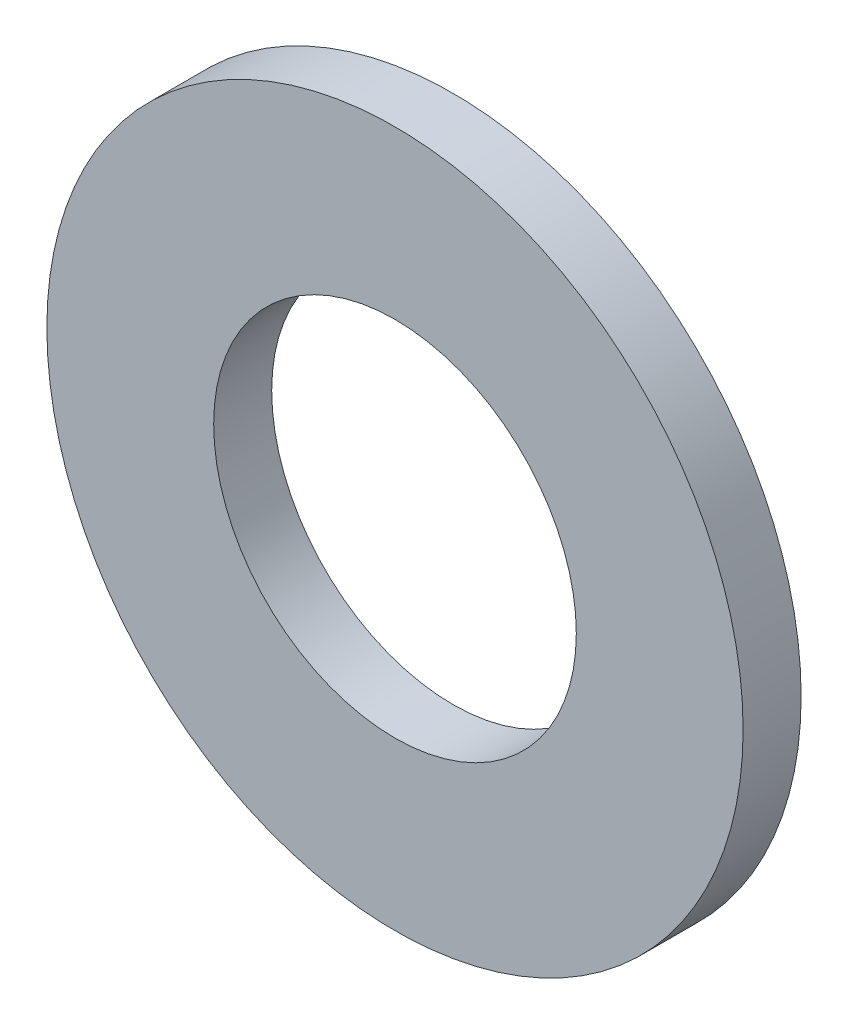
SolidWorks part; units mm, degrees
ref_plane "Ön Düzlem" through (0, 0, 0) normal (0, 0, 1) x (1, 0, 0)
ref_plane "Üst Düzlem" through (0, 0, 0) normal (0, 1, 0) x (1, 0, 0)
ref_plane "Sağ Düzlem" through (0, 0, 0) normal (1, 0, 0) x (0, 0, -1)
sketch "Çizim1" plane through (0, 0, 0) normal (0, 0, 1) x (1, 0, 0)
  circle A0 centre (0, 0) radius 6
  circle A1 centre (0, 0) radius 3.125
  dimension "D1" = 12
  dimension "D2" = 6.25
extrude "Yükseklik-Ekstrüzyon1" add sketch "Çizim1" along normal blind 1
